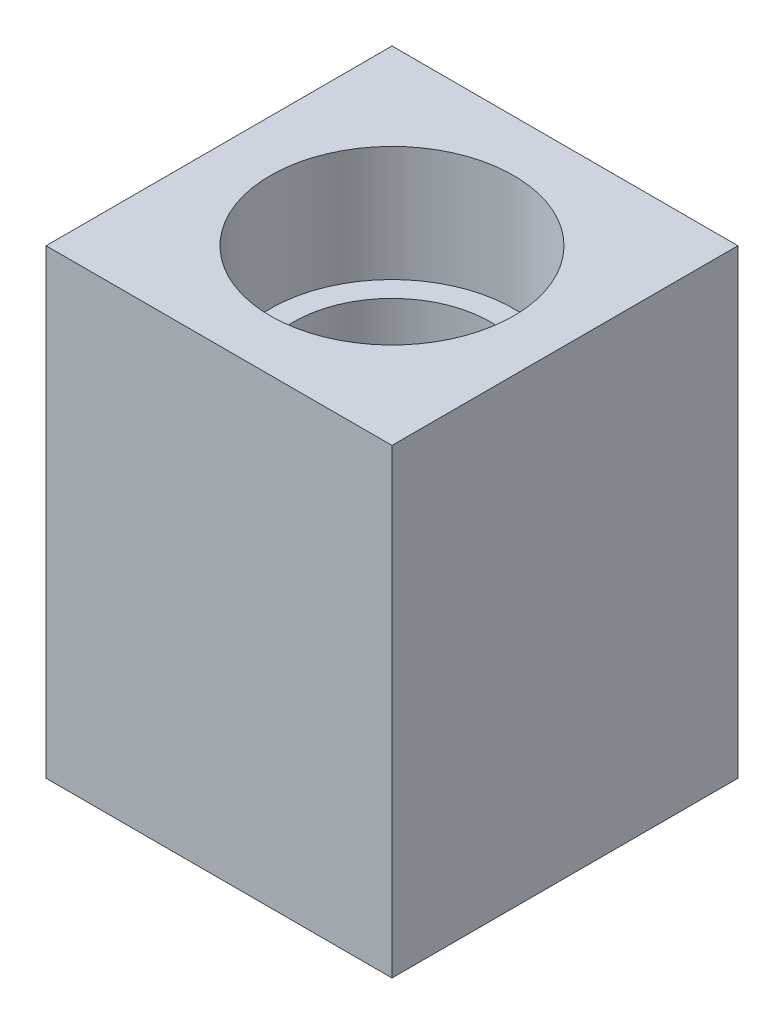
SolidWorks part; units mm, degrees
ref_plane "Front Plane" through (0, 0, 0) normal (0, 0, 1) x (1, 0, 0)
ref_plane "Top Plane" through (0, 0, 0) normal (0, 1, 0) x (1, 0, 0)
ref_plane "Right Plane" through (0, 0, 0) normal (1, 0, 0) x (0, 0, -1)
sketch "Sketch1" plane through (0, 0, 0) normal (0, 1, 0) x (1, 0, 0)
  line L1 (-7.5, -7.5) -> (7.5, -7.5)
  line L2 (-7.5, -7.5) -> (-7.5, 7.5)
  line L3 (-7.5, 7.5) -> (7.5, 7.5)
  line L4 (7.5, -7.5) -> (7.5, 7.5)
  line L5 (-7.5, -7.5) -> (7.5, 7.5) construction
  line L6 (-7.5, 7.5) -> (7.5, -7.5) construction
  point P0 (0, 0)
  dimension "D1" = 15
  dimension "D2" = 15
extrude "Boss-Extrude1" add sketch "Sketch1" along normal blind 20
sketch "Sketch2" plane through (0, 20, 0) normal (0, 1, 0) x (1, 0, 0)
  circle A0 centre (0, 0) radius 4.275
  dimension "D1" = 8.55
extrude "Cut-Extrude1" cut sketch "Sketch2" against normal blind 20
sketch "Sketch3" plane through (0, 20, 0) normal (0, 1, 0) x (1, 0, 0)
  circle A0 centre (0, 0) radius 5.275
  dimension "D1" = 10.55
extrude "Cut-Extrude2" cut sketch "Sketch3" against normal blind 5
